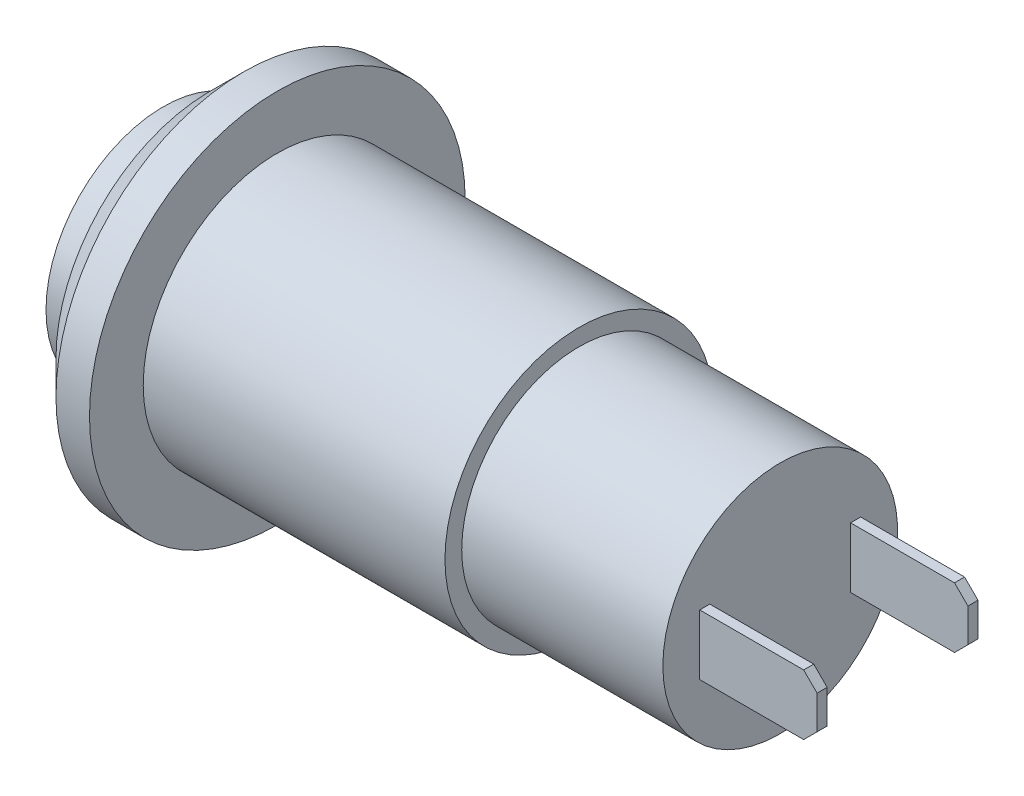
SolidWorks part; units mm, degrees
ref_plane "前视基准面" through (0, 0, 0) normal (0, 0, 1) x (1, 0, 0)
ref_plane "上视基准面" through (0, 0, 0) normal (0, 1, 0) x (1, 0, 0)
ref_plane "右视基准面" through (0, 0, 0) normal (1, 0, 0) x (0, 0, -1)
sketch "草图2" plane through (0, 0, 0) normal (0, 0, 1) x (1, 0, 0)
  line L0 (-3.0927, 0) -> (24.9908, 0) construction
  line L1 (0, 0) -> (0, -3.5)
  line L2 (0, -3.5) -> (1.4, -3.5)
  line L3 (0, 0) -> (18.4, 0)
  line L6 (1.4, -5.6026) -> (1.4, -3.5)
  line L7 (1.4, -5.6026) -> (3.4, -5.6026)
  line L8 (3.4, -5.6026) -> (3.4, -4)
  line L9 (3.4, -4) -> (12.4, -4)
  line L10 (12.4, -4) -> (12.4, -3.5)
  line L11 (12.4, -3.5) -> (18.4, -3.5)
  line L12 (18.4, -3.5) -> (18.4, 0)
  point P9 (0, 0)
  point P10 (0, 0)
  point P17 (0, 0)
  point P19 (0, 0)
  point P20 (0, 0)
  dimension "D1" = 7
  dimension "D2" = 11.2052
  dimension "D3" = 1.4
  dimension "D5" = 8
  dimension "D6" = 18.4
  dimension "D7" = 9
revolve "旋转2" add sketch "草图2" angle 360 about L0
cosmetic thread "装饰螺纹线1" parameters "D2"=6.647
chamfer "倒角1" distance 1 angle 45 1 edges at (1.4, 0, 5.6026)
sketch "草图4" plane through (18.4, 0, 0) normal (1, 0, 0) x (0, 0, -1)
  line L0 (-3.0648, 0) -> (3.0163, 0) construction
  line L1 (0, -2.1946) -> (0, 2.1322) construction
  line L2 (-2.1, -0.9) -> (-2.4, -0.9)
  line L3 (-2.1, -0.9) -> (-2.1, 0.9)
  line L4 (-2.1, 0.9) -> (-2.4, 0.9)
  line L5 (-2.4, -0.9) -> (-2.4, 0.9)
  line L6 (-2.1, -0.9) -> (-2.4, 0.9) construction
  line L7 (-2.1, 0.9) -> (-2.4, -0.9) construction
  line L8 (2.1, -0.9) -> (2.4, -0.9)
  line L9 (2.1, -0.9) -> (2.1, 0.9)
  line L10 (2.1, 0.9) -> (2.4, 0.9)
  line L11 (2.4, -0.9) -> (2.4, 0.9)
  point P3 (-2.25, 0)
  point P8 (-2.25, -0.9)
  dimension "D1" = 1.8
  dimension "D2" = 0.3
  dimension "D3" = 4.8
extrude "凸台-拉伸1" add sketch "草图4" along normal blind 3.5
chamfer "倒角2" distance 0.4 angle 45 4 edges at (21.9, 0.9, 2.25) (21.9, -0.9, 2.25) (21.9, -0.9, -2.25) (21.9, 0.9, -2.25)
